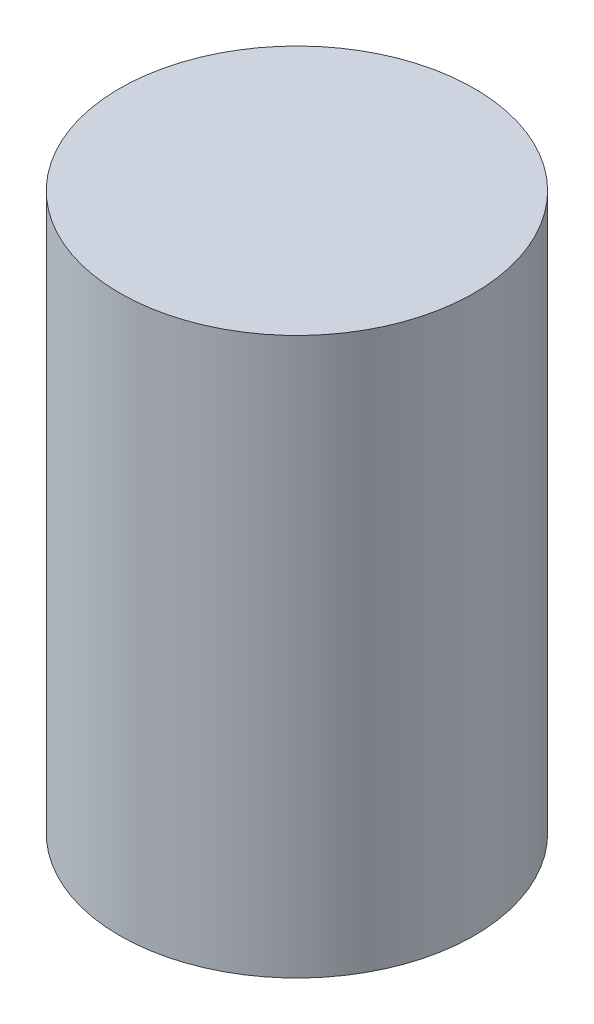
SolidWorks part; units mm, degrees
ref_plane "Front Plane" through (0, 0, 0) normal (0, 0, 1) x (1, 0, 0)
ref_plane "Top Plane" through (0, 0, 0) normal (0, 1, 0) x (1, 0, 0)
ref_plane "Right Plane" through (0, 0, 0) normal (1, 0, 0) x (0, 0, -1)
other "Configuration Table"
sketch "Sketch1" plane through (0, 0, 0) normal (0, 1, 0) x (1, 0, 0)
  circle A0 centre (0, 0) radius 13.8828
extrude "Boss-Extrude1" add sketch "Sketch1" along normal blind 43.5798
